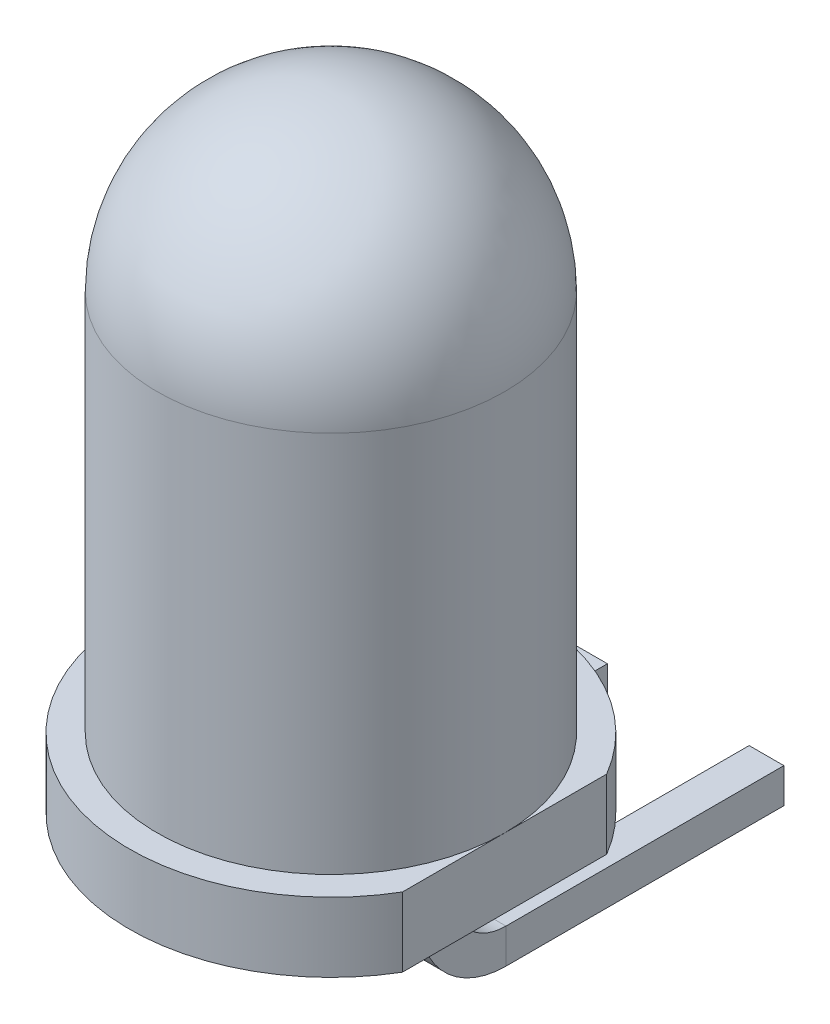
SolidWorks part; units mm, degrees
ref_plane "Front Plane" through (0, 0, 0) normal (0, 0, 1) x (1, 0, 0)
ref_plane "Top Plane" through (0, 0, 0) normal (0, 1, 0) x (1, 0, 0)
ref_plane "Right Plane" through (0, 0, 0) normal (1, 0, 0) x (0, 0, -1)
sketch "Sketch1" plane through (0, 0, 0) normal (0, 0, -1) x (1, 0, 0)
  line L0 (0, 0) -> (0, -9)
  line L1 (2.5, -6.5) -> (2.5, -1)
  line L2 (2.9, 0) -> (0, 0)
  line L3 (2.5, -1) -> (2.9, -1)
  line L4 (2.9, -1) -> (2.9, 0)
  line L5 (0, 0) -> (0, -11.6681) construction
  arc A0 (2.5, -6.5) -> (0, -9) centre (0, -6.5) cw
  dimension "D1" = 5
  dimension "D2" = 5.8
  dimension "D3" = 1
  dimension "D4" = 9
revolve "Revolve1" add sketch "Sketch1" angle 360 about L0
sketch "Sketch2" plane through (0, 0, 0) normal (0, -1, 0) x (-1, 0, 0)
  line L0 (-2.9, -1.4697) -> (-2.9, 1.4697)
  line L1 (-2.9, 1.4697) -> (-2.5, 1.4697)
  line L3 (-2.9, -1.4697) -> (-2.5, -1.4697)
  line L4 (-2.5, 1.4697) -> (-2.5, -1.4697)
  circle A1 centre (0, 0) radius 2.9 construction
  circle A2 centre (0, 0) radius 2.9 construction
  circle A3 centre (0, 0) radius 2.5 construction
extrude "Cut-Extrude1" cut sketch "Sketch2" against normal through all
sketch "Sketch3" plane through (0, 0, 0) normal (0, -1, 0) x (-1, 0, 0)
  line L0 (0, 1.7562) -> (0, 0) construction
  line L1 (0, 0) -> (1.27, 0) construction
  line L2 (-1.02, 0.25) -> (-1.02, -0.25)
  line L3 (1.02, 0.25) -> (1.52, 0.25)
  line L4 (1.02, 0.25) -> (1.02, -0.25)
  line L5 (1.02, -0.25) -> (1.52, -0.25)
  line L6 (1.52, 0.25) -> (1.52, -0.25)
  line L7 (1.02, 0.25) -> (1.52, -0.25) construction
  line L8 (1.02, -0.25) -> (1.52, 0.25) construction
  line L9 (-1.02, -0.25) -> (-1.52, -0.25)
  line L10 (-1.52, 0.25) -> (-1.52, -0.25)
  line L11 (-1.02, 0.25) -> (-1.52, 0.25)
  dimension "D1" = 0.5
  dimension "D2" = 1.27
ref_plane "Plane1" through (-1.27, 0, 0) normal (1, 0, 0) x (0, 0, -1)
sketch "Sketch4" plane through (-1.27, 0, 0) normal (1, 0, 0) x (0, 0, -1)
  line L0 (0, 0) -> (0, -0.4)
  line L1 (1, -1.4) -> (5, -1.4)
  arc A0 (0, -0.4) -> (1, -1.4) centre (1, -0.4) ccw
  dimension "D3" = 5
  dimension "D2" = 1
  dimension "D1" = 0.4
sweep "Sweep1" add profiles "Sketch3" path "Sketch4"
